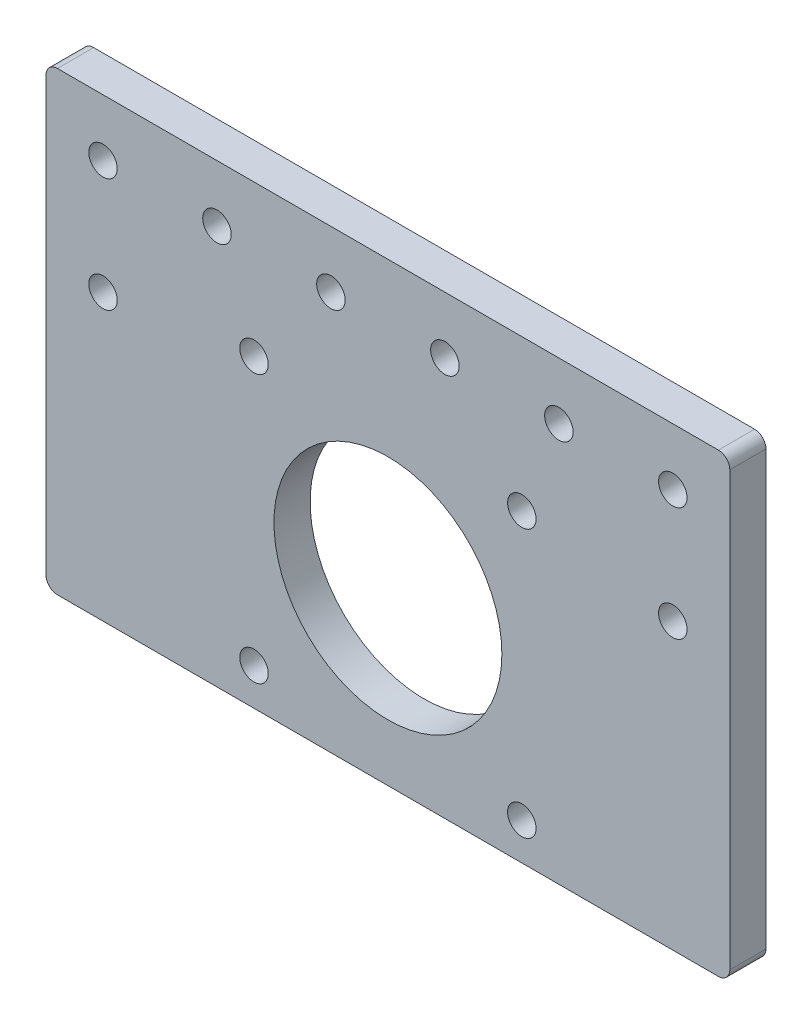
SolidWorks part; units mm, degrees
ref_plane "Front Plane" through (0, 0, 0) normal (0, 0, 1) x (1, 0, 0)
ref_plane "Top Plane" through (0, 0, 0) normal (0, 1, 0) x (1, 0, 0)
ref_plane "Right Plane" through (0, 0, 0) normal (1, 0, 0) x (0, 0, -1)
sketch "Sketch1" plane through (0, 0, 0) normal (0, 0, 1) x (1, 0, 0)
  line L0 (-60, 30) -> (60, 30) construction
  line L1 (-60, 40) -> (60, 40)
  line L2 (-60, 40) -> (-60, -40)
  line L3 (-60, -40) -> (60, -40)
  line L4 (60, 40) -> (60, -40)
  line L5 (-60, 40) -> (60, -40) construction
  line L6 (-60, -40) -> (60, 40) construction
  line L7 (-50, 40) -> (-50, -40) construction
  line L8 (0, -10) -> (-23.5, -10) construction
  line L9 (-23.5, -10) -> (-23.5, 13.5) construction
  circle A0 centre (-50, 30) radius 2.5
  circle A1 centre (-30, 30) radius 2.5
  circle A2 centre (-10, 30) radius 2.5
  circle A3 centre (10, 30) radius 2.5
  circle A4 centre (30, 30) radius 2.5
  circle A5 centre (50, 30) radius 2.5
  circle A6 centre (-50, 10) radius 2.5
  circle A7 centre (50, 10) radius 2.5
  circle A8 centre (0, -10) radius 20
  circle A9 centre (-23.5, 13.5) radius 2.5
  circle A10 centre (23.5, 13.5) radius 2.5
  circle A11 centre (23.5, -33.5) radius 2.5
  circle A12 centre (-23.5, -33.5) radius 2.5
  point P0 (0, 0)
  point P10 (-50, 30)
  point P41 (0, -10)
  dimension "D5" = 5
  dimension "D9" = 40
  dimension "D12" = 5
  dimension "D1" = 120
  dimension "D2" = 80
  dimension "D3" = 10
  dimension "D4" = 10
  dimension "D8" = 40
  dimension "D10" = 23.5
  dimension "D11" = 23.5
  dimension "D6" = 6
  dimension "D7" = 2
  dimension "D13" = 4
extrude "Boss-Extrude1" add sketch "Sketch1" along normal blind 6.35
fillet "Fillet1" radius 2 4 edges at (60, -40, 3.175) (-60, -40, 3.175) (60, 40, 3.175) (-60, 40, 3.175)
